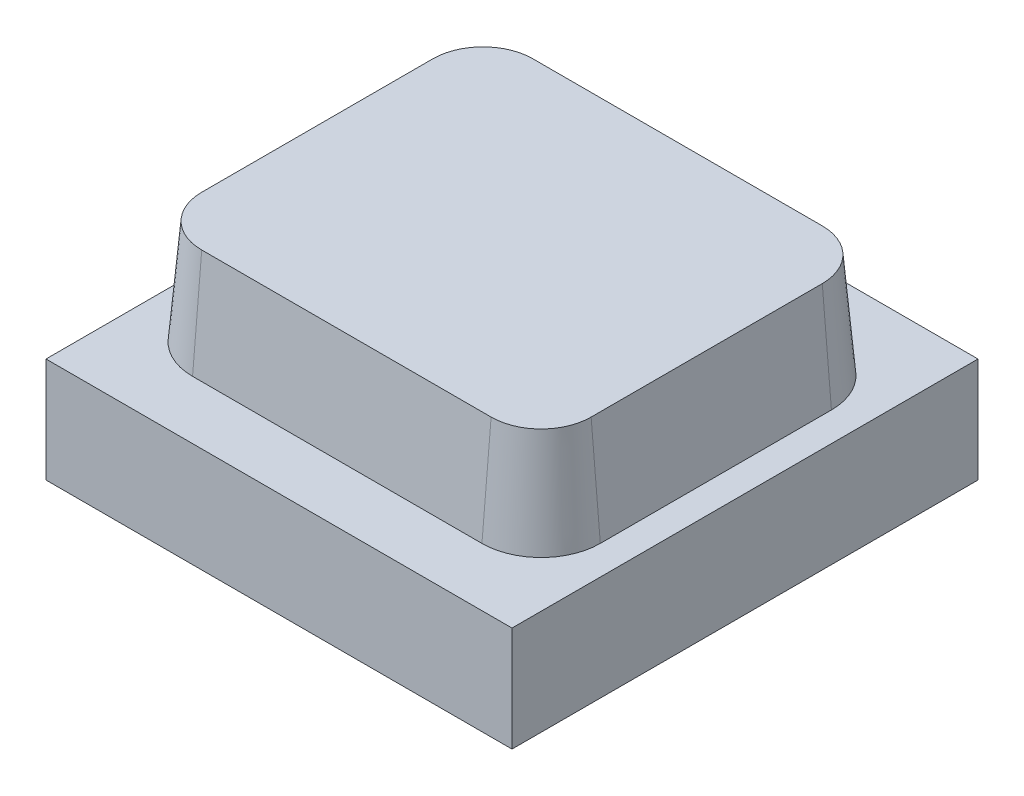
SolidWorks part; units mm, degrees
ref_plane "Front Plane" through (0, 0, 0) normal (0, 0, 1) x (1, 0, 0)
ref_plane "Top Plane" through (0, 0, 0) normal (0, 1, 0) x (1, 0, 0)
ref_plane "Right Plane" through (0, 0, 0) normal (1, 0, 0) x (0, 0, -1)
sketch "Sketch1" plane through (0, 0, 0) normal (0, 1, 0) x (1, 0, 0)
  line L1 (-1, 1) -> (1, 1)
  line L2 (-1, 1) -> (-1, -1)
  line L3 (-1, -1) -> (1, -1)
  line L4 (1, 1) -> (1, -1)
  point P4 (0, 1)
  point P5 (1, 0)
  point P6 (0, 0)
  point P8 (0, 0)
  point P9 (0, 0)
  dimension "D1" = 2
  dimension "D2" = 2
extrude "Boss-Extrude1" add sketch "Sketch1" along normal blind 0.45
sketch "Sketch2" plane through (0, 0.45, 0) normal (0, 1, 0) x (1, 0, 0)
  line L1 (-0.621, 0.75) -> (0.621, 0.75)
  line L2 (-0.875, 0.496) -> (-0.875, -0.496)
  line L3 (-0.621, -0.75) -> (0.621, -0.75)
  line L4 (0.875, 0.496) -> (0.875, -0.496)
  arc A0 (-0.875, -0.496) -> (-0.621, -0.75) centre (-0.621, -0.496) ccw
  arc A1 (0.621, -0.75) -> (0.875, -0.496) centre (0.621, -0.496) ccw
  arc A2 (0.621, 0.75) -> (0.875, 0.496) centre (0.621, 0.496) cw
  arc A3 (-0.621, 0.75) -> (-0.875, 0.496) centre (-0.621, 0.496) ccw
  point P4 (0, 0.75)
  point P5 (0.875, 0)
  point P6 (0, 0)
  point P7 (0, 0)
  point P9 (0, 0)
  point P18 (-2.1034, -1.2846)
  point P19 (0.2006, 0.8102)
  point P20 (0.6482, 0.4912)
  point P21 (0.4747, -0.7287)
  point P22 (0.8675, -0.6135)
  dimension "D1" = 0.254
  dimension "D2" = 1.75
  dimension "D3" = 1.5
extrude "Boss-Extrude2" add sketch "Sketch2" along normal offset from surface 0.9 draft 5 separate body
